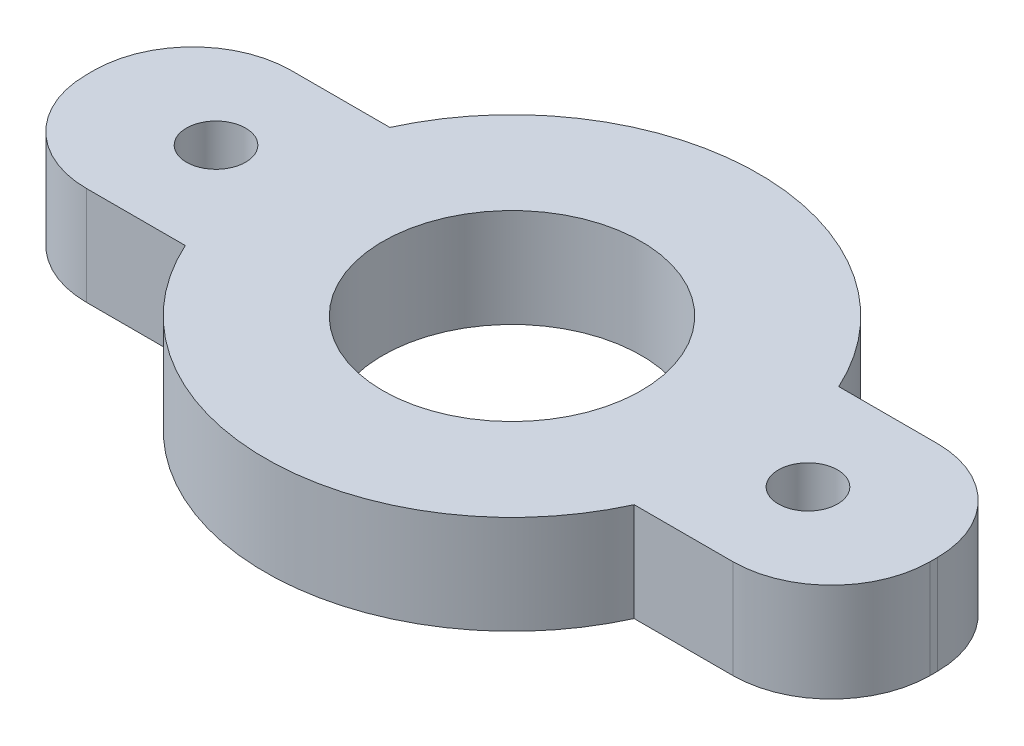
SolidWorks part; units mm, degrees
ref_plane "Front Plane" through (0, 0, 0) normal (0, 0, 1) x (1, 0, 0)
ref_plane "Top Plane" through (0, 0, 0) normal (0, 1, 0) x (1, 0, 0)
ref_plane "Right Plane" through (0, 0, 0) normal (1, 0, 0) x (0, 0, -1)
sketch "Sketch1" plane through (0, 0, 0) normal (0, 1, 0) x (1, 0, 0)
  line L0 (-15, 0) -> (15, 0) construction
  line L1 (-11.3745, 5.1837) -> (-16.3745, 5.1837)
  line L2 (16.3745, -5.1837) -> (11.3745, -5.1837)
  line L3 (21.3745, -0.1837) -> (21.3745, 0.1837)
  line L4 (16.3745, 5.1837) -> (11.3745, 5.1837)
  line L5 (-21.3745, -0.1837) -> (-21.3745, 0.1837)
  line L8 (-11.3745, -5.1837) -> (-16.3745, -5.1837)
  circle A0 centre (0, 0) radius 6.55
  circle A1 centre (-15, 0) radius 1.5
  circle A2 centre (15, 0) radius 1.5
  arc A3 (-11.3745, -5.1837) -> (11.3745, -5.1837) centre (0, 0) ccw
  arc A4 (11.3745, 5.1837) -> (-11.3745, 5.1837) centre (0, 0) ccw
  arc A5 (-21.3745, -0.1837) -> (-16.3745, -5.1837) centre (-16.3745, -0.1837) ccw
  arc A6 (-16.3745, 5.1837) -> (-21.3745, 0.1837) centre (-16.3745, 0.1837) ccw
  arc A7 (21.3745, -0.1837) -> (16.3745, -5.1837) centre (16.3745, -0.1837) cw
  arc A8 (21.3745, 0.1837) -> (16.3745, 5.1837) centre (16.3745, 0.1837) ccw
  dimension "D1" = 3
  dimension "D2" = 13.1
  dimension "D4" = 25
  dimension "D5" = 5
  dimension "D8" = 5
  dimension "D3" = 30
  dimension "D6" = 10
  dimension "D7" = 5
  dimension "D9" = 10
extrude "Boss-Extrude1" add sketch "Sketch1" along normal blind 5
